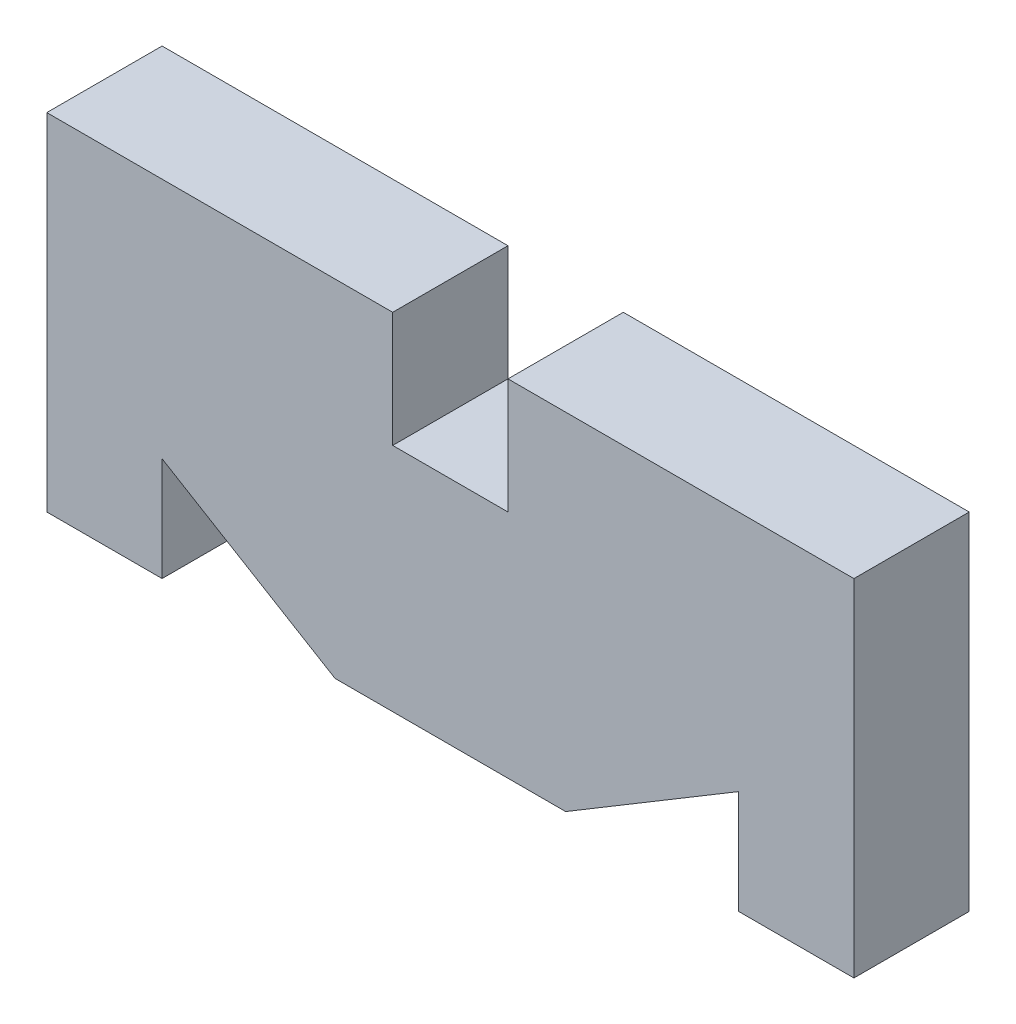
SolidWorks part; units mm, degrees
ref_plane "Front Plane" through (0, 0, 0) normal (0, 0, 1) x (1, 0, 0)
ref_plane "Top Plane" through (0, 0, 0) normal (0, 1, 0) x (1, 0, 0)
ref_plane "Right Plane" through (0, 0, 0) normal (1, 0, 0) x (0, 0, -1)
sketch "Sketch2" plane through (0, 0, 0) normal (0, 0, 1) x (1, 0, 0)
  line L0 (-22.9783, 22.9783) -> (-22.9783, -7.0217)
  line L1 (-22.9783, -7.0217) -> (-12.9783, -7.0217)
  line L2 (-12.9783, -7.0217) -> (-12.9783, 1.9783)
  line L3 (-12.9783, 1.9783) -> (2.0217, -7.0217)
  line L4 (2.0217, -7.0217) -> (22.0217, -7.0217)
  line L6 (17.0217, 12.9783) -> (7.0217, 12.9783)
  line L7 (7.0217, 12.9783) -> (7.0217, 22.9783)
  line L8 (7.0217, 22.9783) -> (-22.9783, 22.9783)
  line L9 (17.0217, 12.9783) -> (17.0217, 22.9783)
  line L10 (37.0217, 1.9783) -> (22.0217, -7.0217)
  line L11 (37.0217, -7.0217) -> (37.0217, 1.9783)
  line L12 (47.0217, -7.0217) -> (37.0217, -7.0217)
  line L13 (47.0217, 22.9783) -> (47.0217, -7.0217)
  line L14 (17.0217, 22.9783) -> (47.0217, 22.9783)
  dimension "D1" = 30
  dimension "D2" = 30
  dimension "D3" = 10
  dimension "D4" = 15
  dimension "D7" = 10
extrude "Boss-Extrude1" add sketch "Sketch2" along normal blind 10
